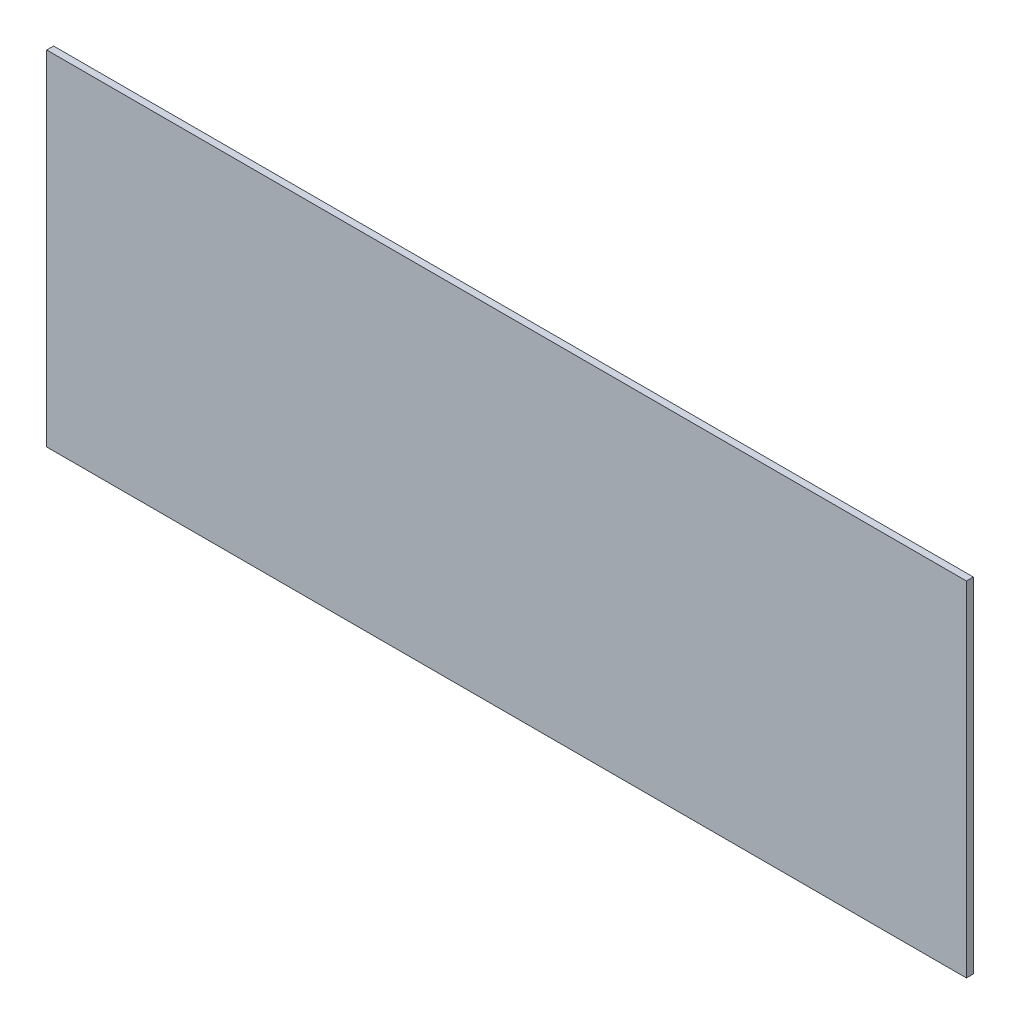
SolidWorks part; units mm, degrees
material "Akryl (středně-vysoký dopad)"
ref_plane "Přední rovina" through (0, 0, 0) normal (0, 0, 1) x (1, 0, 0)
ref_plane "Horní rovina" through (0, 0, 0) normal (0, 1, 0) x (1, 0, 0)
ref_plane "Pravá rovina" through (0, 0, 0) normal (1, 0, 0) x (0, 0, -1)
sketch "Skica1" plane through (0, 0, 0) normal (0, 0, 1) x (1, 0, 0)
  line L1 (267.5, -100) -> (-267.5, -100)
  line L2 (267.5, -100) -> (267.5, 100)
  line L3 (267.5, 100) -> (-267.5, 100)
  line L4 (-267.5, -100) -> (-267.5, 100)
  line L5 (267.5, -100) -> (-267.5, 100) construction
  line L6 (267.5, 100) -> (-267.5, -100) construction
  point P0 (0, 0)
  dimension "D1" = 535
  dimension "D2" = 200
extrude "Přidat vysunutím1" add sketch "Skica1" along normal blind 4
